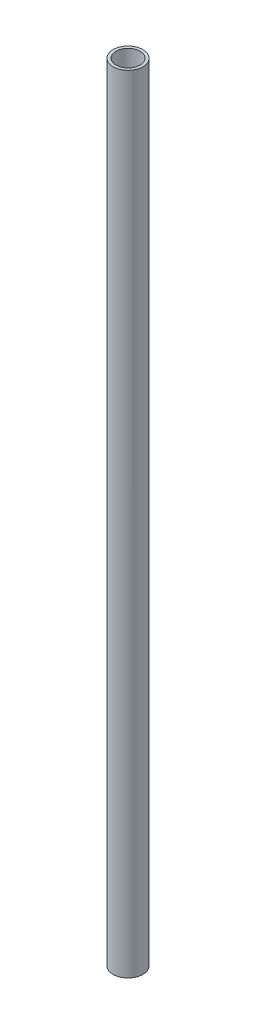
SolidWorks part; units mm, degrees
ref_plane "Front Plane" through (0, 0, 0) normal (0, 0, 1) x (1, 0, 0)
ref_plane "Top Plane" through (0, 0, 0) normal (0, 1, 0) x (1, 0, 0)
ref_plane "Right Plane" through (0, 0, 0) normal (1, 0, 0) x (0, 0, -1)
sketch "Sketch1" plane through (0, 0, 0) normal (0, 1, 0) x (1, 0, 0)
  circle A0 centre (0, 0) radius 0.3977
  circle A1 centre (0, 0) radius 0.3215
  dimension "D1" = 0.643
  dimension "D2" = 0.0762
extrude "Boss-Extrude1" add sketch "Sketch1" along normal up to surface (21 mm away)
